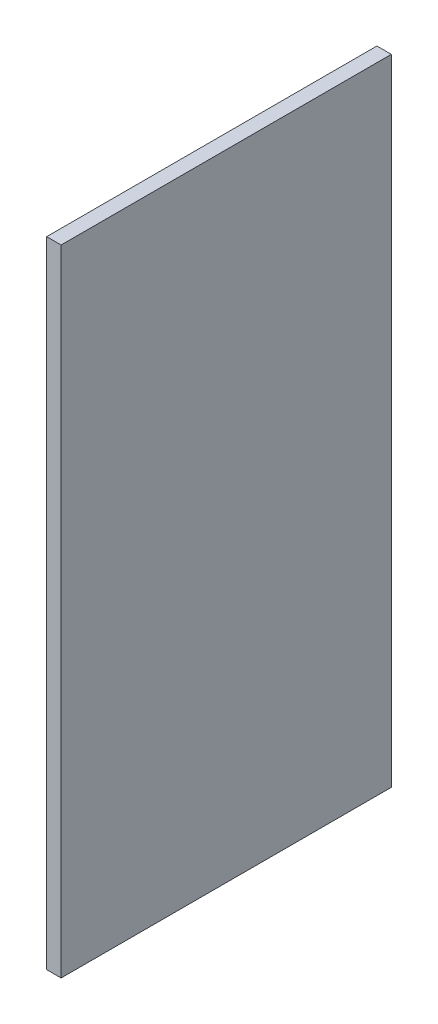
SolidWorks part; units mm, degrees
material "Teak"
ref_plane "Front Plane" through (0, 0, 0) normal (0, 0, 1) x (1, 0, 0)
ref_plane "Top Plane" through (0, 0, 0) normal (0, 1, 0) x (1, 0, 0)
ref_plane "Right Plane" through (0, 0, 0) normal (1, 0, 0) x (0, 0, -1)
sketch "Sketch1" plane through (0, 0, 0) normal (1, 0, 0) x (0, 0, -1)
  line L1 (0, 0) -> (412, 0)
  line L2 (0, 0) -> (0, 792)
  line L3 (0, 792) -> (412, 792)
  line L4 (412, 0) -> (412, 792)
  dimension "D1" = 412
  dimension "D2" = 792
extrude "Boss-Extrude1" add sketch "Sketch1" along normal blind 18 contours L3 L4 L1 L2
